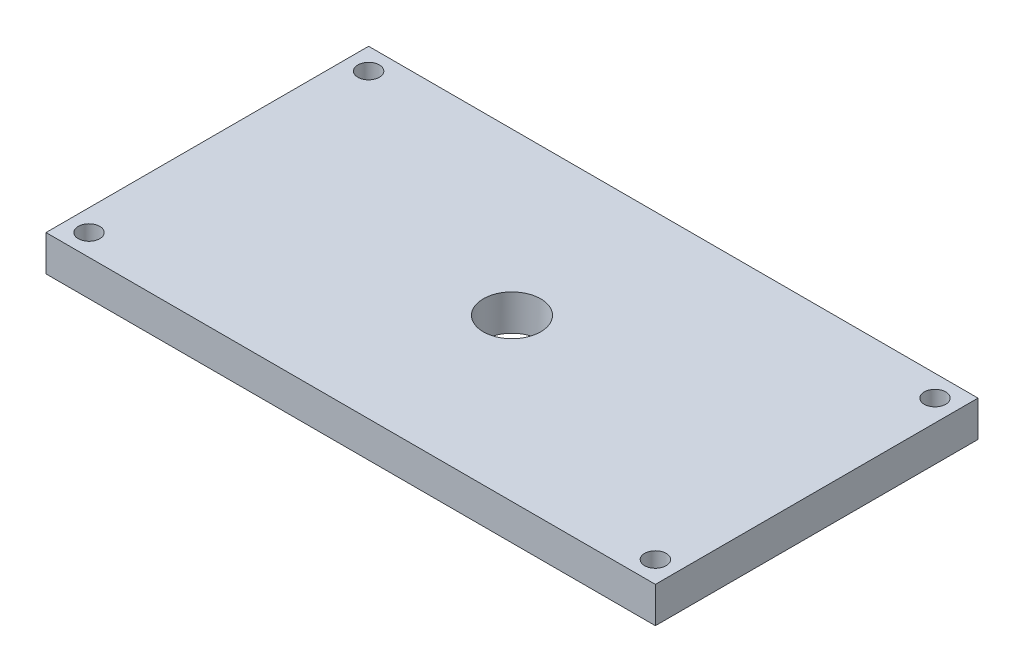
SolidWorks part; units mm, degrees
ref_plane "Front Plane" through (0, 0, 0) normal (0, 0, 1) x (1, 0, 0)
ref_plane "Top Plane" through (0, 0, 0) normal (0, 1, 0) x (1, 0, 0)
ref_plane "Right Plane" through (0, 0, 0) normal (1, 0, 0) x (0, 0, -1)
sketch "Sketch1" plane through (0, 0, 0) normal (0, 1, 0) x (1, 0, 0)
  line L1 (0, 0) -> (85, 0)
  line L2 (0, 0) -> (0, 45)
  line L3 (0, 45) -> (85, 45)
  line L4 (85, 0) -> (85, 45)
  dimension "D1" = 85
  dimension "D2" = 45
extrude "Boss-Extrude1" add sketch "Sketch1" along normal blind 5
sketch "Sketch2" plane through (0, 5, 0) normal (0, 1, 0) x (1, 0, 0)
  line L0 (0, 45) -> (0, 0) construction
  line L1 (85, 45) -> (0, 45) construction
  line L2 (0, 0) -> (85, 0) construction
  line L3 (85, 0) -> (85, 45) construction
  circle A0 centre (3, 42) radius 1.5
  circle A1 centre (3, 3) radius 1.5
  circle A2 centre (82, 3) radius 1.5
  circle A3 centre (82, 42) radius 1.5
  dimension "D1" = 3
  dimension "D2" = 3
  dimension "D3" = 3
  dimension "D4" = 3
  dimension "D5" = 3
  dimension "D6" = 3
  dimension "D7" = 3
  dimension "D8" = 3
  dimension "D9" = 3
  dimension "D10" = 3
  dimension "D11" = 3
  dimension "D12" = 3
extrude "Cut-Extrude1" cut sketch "Sketch2" against normal blind 5
sketch "Sketch3" plane through (0, 5, 0) normal (0, 1, 0) x (1, 0, 0)
  line L0 (85, 45) -> (0, 45) construction
  line L1 (0, 45) -> (0, 0) construction
  circle A0 centre (42.5, 22.5) radius 4
  point P4 (42.5, 45)
  dimension "D1" = 22.5
  dimension "D2" = 42.5
  dimension "D3" = 8
extrude "Cut-Extrude2" cut sketch "Sketch3" against normal blind 10
